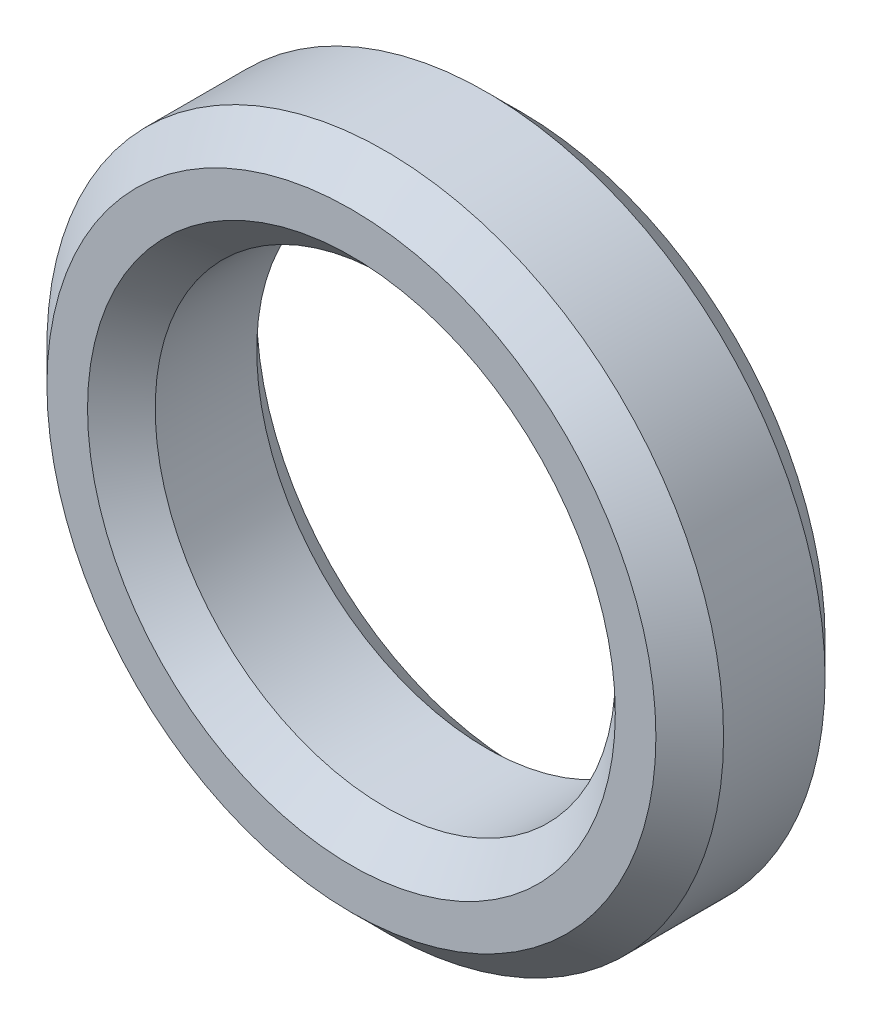
SolidWorks part; units mm, degrees
ref_plane "Front Plane" through (0, 0, 0) normal (0, 0, 1) x (1, 0, 0)
ref_plane "Top Plane" through (0, 0, 0) normal (0, 1, 0) x (1, 0, 0)
ref_plane "Right Plane" through (0, 0, 0) normal (1, 0, 0) x (0, 0, -1)
sketch "Sketch1" plane through (0, 0, 0) normal (0, 0, 1) x (1, 0, 0)
  circle A0 centre (0, 0) radius 10
  circle A1 centre (0, 0) radius 7
  dimension "D1" = 20
  dimension "D2" = 14
extrude "Main Body Extrude" add sketch "Sketch1" along normal mid plane 5 contours A0 A1
other ".2 Offset" face at (7, 0, 2.5) parameters "D1"=0.2
chamfer "Chamfer1" distance 1 angle 45 4 edges at (6.8, 0, 2.5) (10, 0, 2.5) (6.8, 0, -2.5) (10, 0, -2.5)
